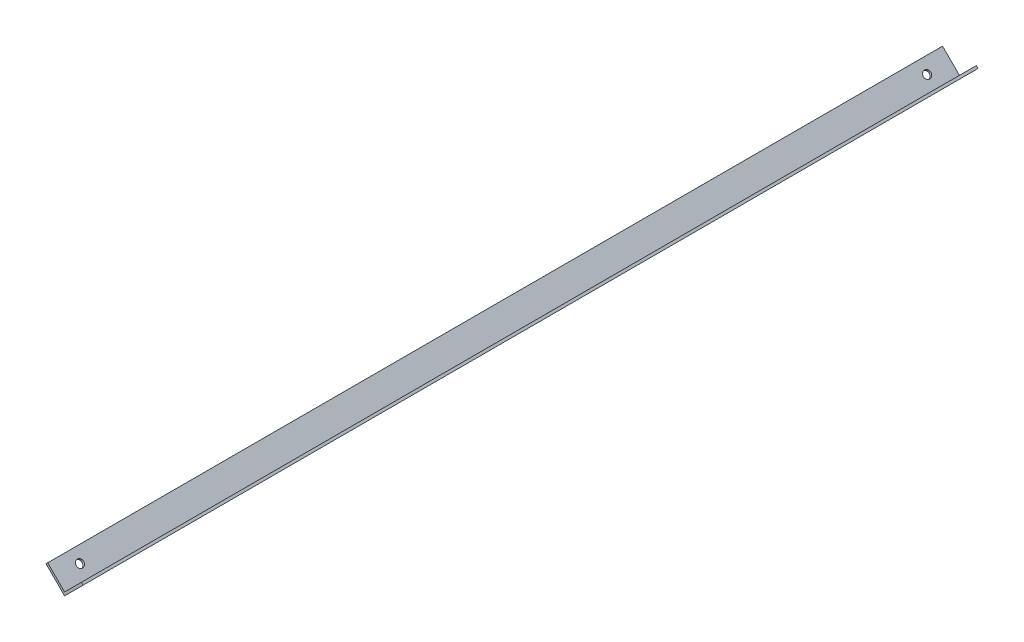
SolidWorks part; units mm, degrees
material "6061 Alloy"
ref_plane "Front Plane" through (0, 0, 0) normal (0, 0, 1) x (1, 0, 0)
ref_plane "Top Plane" through (0, 0, 0) normal (0, 1, 0) x (1, 0, 0)
ref_plane "Right Plane" through (0, 0, 0) normal (1, 0, 0) x (0, 0, -1)
sketch "Sketch1" plane through (0, 0, 0) normal (0, 0, 1) x (1, 0, 0)
  line L0 (0, 0) -> (-8.9803, 8.9803)
  line L1 (-8.9803, 8.9803) -> (-9.8783, 8.0822)
  line L2 (-9.8783, 8.0822) -> (0, -1.7961)
  line L3 (0, -1.7961) -> (9.8783, 8.0822)
  line L4 (9.8783, 8.0822) -> (8.9803, 8.9803)
  line L5 (8.9803, 8.9803) -> (0, 0)
  line L6 (-13.872, 0) -> (16.6117, 0) construction
  dimension "D1" = 1.27
  dimension "D2" = 12.7
extrude "Boss-Extrude1" add sketch "Sketch1" along normal blind 476.25
sketch "Sketch2" plane through (0, 0, 0) normal (-0.7071, 0.7071, 0) x (0, 0, 1)
  line L0 (0, 12.7) -> (476.25, 12.7) construction
  line L1 (476.25, 12.7) -> (476.25, 0) construction
  circle A0 centre (469.9, 6.35) radius 1.9844
  circle A1 centre (457.2, 6.35) radius 1.9844
  dimension "D2" = 3.9688
  dimension "D1" = 6.35
  dimension "D3" = 6.35
  dimension "D4" = 6.35
  dimension "D5" = 19.05
sketch "Sketch3" plane through (0, 0, 0) normal (0.7071, 0.7071, 0) x (0, 0, -1)
  line L0 (-476.25, 0) -> (-476.25, 12.7) construction
  line L1 (0, 12.7) -> (-476.25, 12.7) construction
  circle A0 centre (-463.55, 6.35) radius 1.9844
  dimension "D2" = 3.9688
  dimension "D1" = 12.7
  dimension "D3" = 6.35
extrude "Cut-Extrude1" cut sketch "Sketch2" against normal through all
extrude "Cut-Extrude2" cut sketch "Sketch3" against normal through all
sketch "Sketch4" plane through (0, 0, 0) normal (-0.7071, 0.7071, 0) x (0, 0, 1)
  line L0 (476.25, 12.7) -> (0, 12.7) construction
  line L1 (0, 12.7) -> (0, 0) construction
  circle A0 centre (6.35, 6.35) radius 1.9844
  circle A1 centre (19.05, 6.35) radius 1.9844
  dimension "D4" = 3.9688
  dimension "D5" = 19.05
  dimension "D1" = 6.35
  dimension "D2" = 6.35
  dimension "D3" = 6.35
sketch "Sketch5" plane through (0, 0, 0) normal (0.7071, 0.7071, 0) x (0, 0, -1)
  line L0 (-476.25, 12.7) -> (0, 12.7) construction
  line L1 (0, 0) -> (0, 12.7) construction
  circle A0 centre (-12.7, 6.35) radius 1.9844
  dimension "D1" = 3.9688
  dimension "D2" = 6.35
  dimension "D3" = 12.7
extrude "Cut-Extrude3" cut sketch "Sketch4" against normal through all
extrude "Cut-Extrude4" cut sketch "Sketch5" against normal through all
